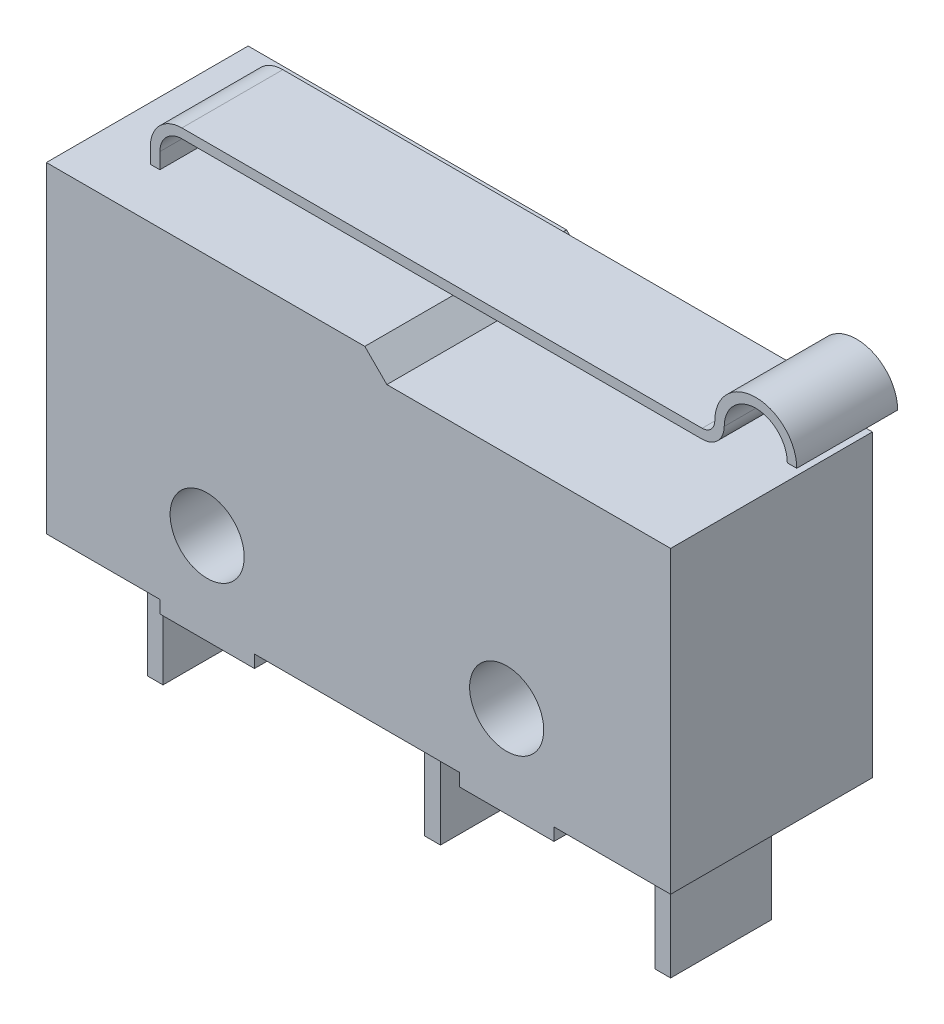
SolidWorks part; units mm, degrees
ref_plane "Front Plane" through (0, 0, 0) normal (0, 0, 1) x (1, 0, 0)
ref_plane "Top Plane" through (0, 0, 0) normal (0, 1, 0) x (1, 0, 0)
ref_plane "Right Plane" through (0, 0, 0) normal (1, 0, 0) x (0, 0, -1)
sketch "Sketch1" plane through (0, 0, 0) normal (0, 0, 1) x (1, 0, 0)
  line L0 (-9.9, 0) -> (9.9, 0) construction
  line L1 (-9.9, 7.7) -> (0.2, 7.7)
  line L2 (-9.9, 7.7) -> (-9.9, -2.5)
  line L3 (-6.3, -2.9) -> (-3.3, -2.9)
  line L4 (9.9, 7) -> (9.9, -2.5)
  line L5 (-9.9, -2.5) -> (-6.3, -2.5)
  line L6 (0.2, 7.7) -> (0.9, 7)
  line L7 (0.9, 7) -> (9.9, 7)
  line L8 (-6.3, -2.5) -> (-6.3, -2.9)
  line L9 (-3.3, -2.9) -> (-3.3, -2.5)
  line L10 (3.2, -2.5) -> (3.2, -2.9)
  line L11 (6.2, -2.5) -> (6.2, -2.9)
  line L12 (3.2, -2.9) -> (6.2, -2.9)
  line L13 (-3.3, -2.5) -> (3.2, -2.5)
  line L14 (6.2, -2.5) -> (9.9, -2.5)
  line L15 (-4.8, -2.9) -> (-4.8, 0) construction
  line L16 (4.7, -2.9) -> (4.7, 0) construction
  circle A0 centre (-4.8, 0) radius 1.175
  circle A1 centre (4.7, 0) radius 1.175
  dimension "D8" = 5.1
  dimension "D9" = 9.5
  dimension "D10" = 2.35
  dimension "D2" = 2.9
  dimension "D3" = 2.5
  dimension "D4" = 9.5
  dimension "D5" = 10.2
  dimension "D6" = 45
  dimension "D7" = 9
  dimension "D11" = 19.8
  dimension "D12" = 3
extrude "Boss-Extrude1" add sketch "Sketch1" along normal mid plane 6.4
sketch "Sketch2" plane through (0, 0, 0) normal (0, 0, 1) x (1, 0, 0)
  line L0 (-9.9, -2.5) -> (-6.3, -2.5) construction
  line L1 (-8.3, -2.5) -> (-7.8, -2.5)
  line L2 (-8.3, -2.5) -> (-8.3, -6.4)
  line L3 (-8.3, -6.4) -> (-7.8, -6.4)
  line L4 (-7.8, -2.5) -> (-7.8, -6.4)
  line L5 (6.2, -2.5) -> (9.9, -2.5) construction
  line L6 (0.5, -2.5) -> (1, -2.5)
  line L7 (0.5, -2.5) -> (0.5, -6.4)
  line L8 (0.5, -6.4) -> (1, -6.4)
  line L9 (1, -2.5) -> (1, -6.4)
  line L10 (7.8, -2.5) -> (8.3, -2.5)
  line L11 (7.8, -2.5) -> (7.8, -6.4)
  line L12 (7.8, -6.4) -> (8.3, -6.4)
  line L13 (8.3, -2.5) -> (8.3, -6.4)
  line L14 (-3.3, -2.5) -> (3.2, -2.5) construction
  line L15 (-9.9, 7.7) -> (-9.9, -2.5) construction
  circle A0 centre (-4.8, 0) radius 1.175 construction
  dimension "D5" = 6.4
  dimension "D1" = 1.6
  dimension "D2" = 8.8
  dimension "D3" = 7.3
  dimension "D4" = 0.5
extrude "Boss-Extrude2" add sketch "Sketch2" along normal mid plane 3.2 separate body
sketch "Sketch3" plane through (0, 0, 0) normal (0, 0, 1) x (1, 0, 0)
  line L0 (-7.9, 7.7) -> (-7.9, 8.2)
  line L1 (0.2, 7.7) -> (-9.9, 7.7) construction
  line L2 (-7.2, 8.9) -> (9.3, 8.9)
  line L3 (-9.9, 7.7) -> (-9.9, -2.5) construction
  arc A0 (-7.9, 8.2) -> (-7.2, 8.9) centre (-7.2, 8.2) cw
  arc A1 (9.3, 8.9) -> (10, 9.6) centre (9.3, 9.6) ccw
  arc A2 (10, 9.6) -> (12, 9.6) centre (11, 9.6) cw
  circle A3 centre (-4.8, 0) radius 1.175 construction
  circle A4 centre (4.7, 0) radius 1.175 construction
  dimension "D1" = 2
  dimension "D2" = 1
  dimension "D3" = 0.7
  dimension "D5" = 15.8
  dimension "D6" = 10.6
  dimension "D4" = 1.2
extrude "Extrude-Thin1" add sketch "Sketch3" along normal mid plane 3.2 separate body thin thin type one direction reverse wall 0.3
